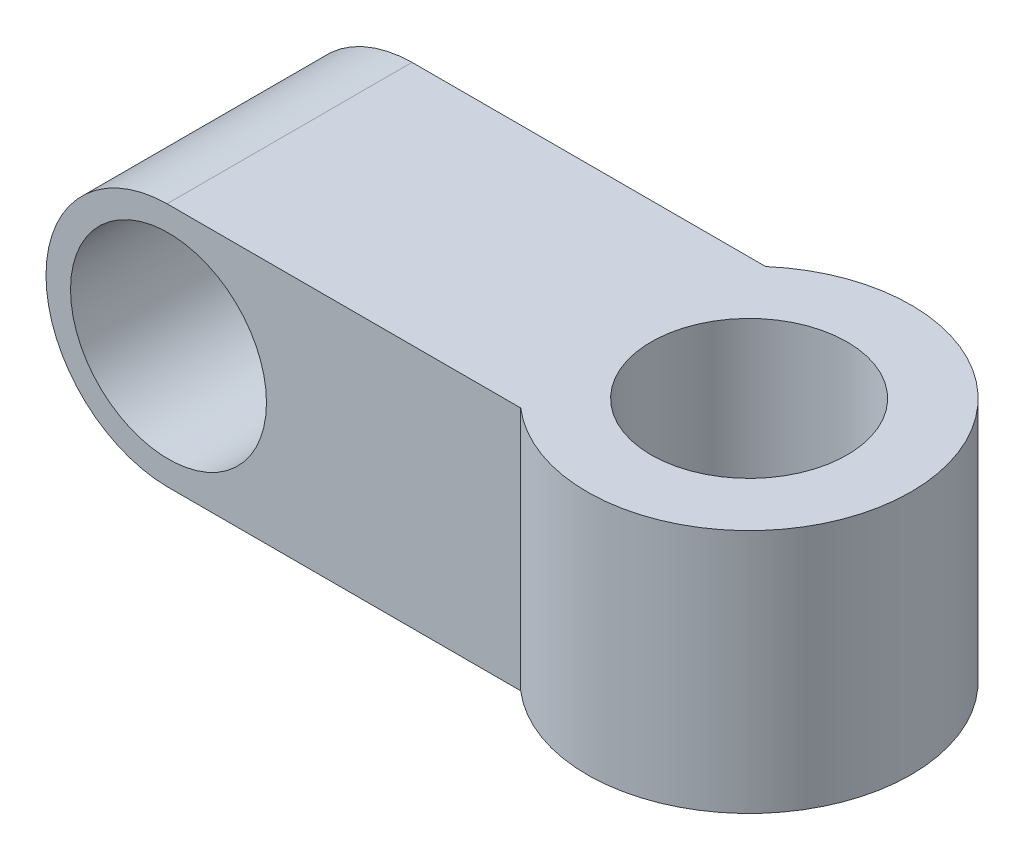
SolidWorks part; units mm, degrees
material "聚亚安酯(11671)"
ref_plane "前视基准面" through (0, 0, 0) normal (0, 0, 1) x (1, 0, 0)
ref_plane "上视基准面" through (0, 0, 0) normal (0, 1, 0) x (1, 0, 0)
ref_plane "右视基准面" through (0, 0, 0) normal (1, 0, 0) x (0, 0, -1)
sketch "草图1" plane through (0, 0, 0) normal (0, 1, 0) x (1, 0, 0)
  circle A0 centre (0, 0) radius 2
  circle A1 centre (0, 0) radius 3.3054
extrude "凸台-拉伸1" add sketch "草图1" along normal blind 5
sketch "草图4" plane through (0, 0, 0) normal (0, 0, 1) x (1, 0, 0)
  line L0 (0, 2.5) -> (-9.3514, 2.5) construction
  line L1 (0, 0) -> (-9.3803, 0)
  line L2 (0, 5) -> (-9.3803, 5)
  line L3 (3.3054, 5) -> (-3.3054, 5) construction
  line L4 (-3.3054, 0) -> (3.3054, 0) construction
  line L5 (-3.3054, 5) -> (-3.3054, 0)
  line L6 (-3.3054, 5) -> (-3.3054, 0) construction
  line L7 (0, 5) -> (0, 0)
  arc A1 (-9.3803, 5) -> (-9.3803, 0) centre (-9.3514, 2.5) ccw
  point P2 (-3.1554, 2.5)
  point P15 (-9.3803, 5)
extrude "凸台-拉伸2" add sketch "草图4" along normal mid plane 5 contours L0 L7 L2 L5 | L7 L0 L5 L1
sketch "草图5" plane through (0, 5, 0) normal (0, 1, 0) x (1, 0, 0)
  circle A0 centre (0, 0) radius 2
extrude "切除-拉伸1" cut sketch "草图5" against normal blind 5
sketch "草图6" plane through (0, 0, 2.5) normal (0, 0, 1) x (1, 0, 0)
  circle A0 centre (-9.3514, 2.5) radius 2
extrude "切除-拉伸2" cut sketch "草图6" against normal through all
